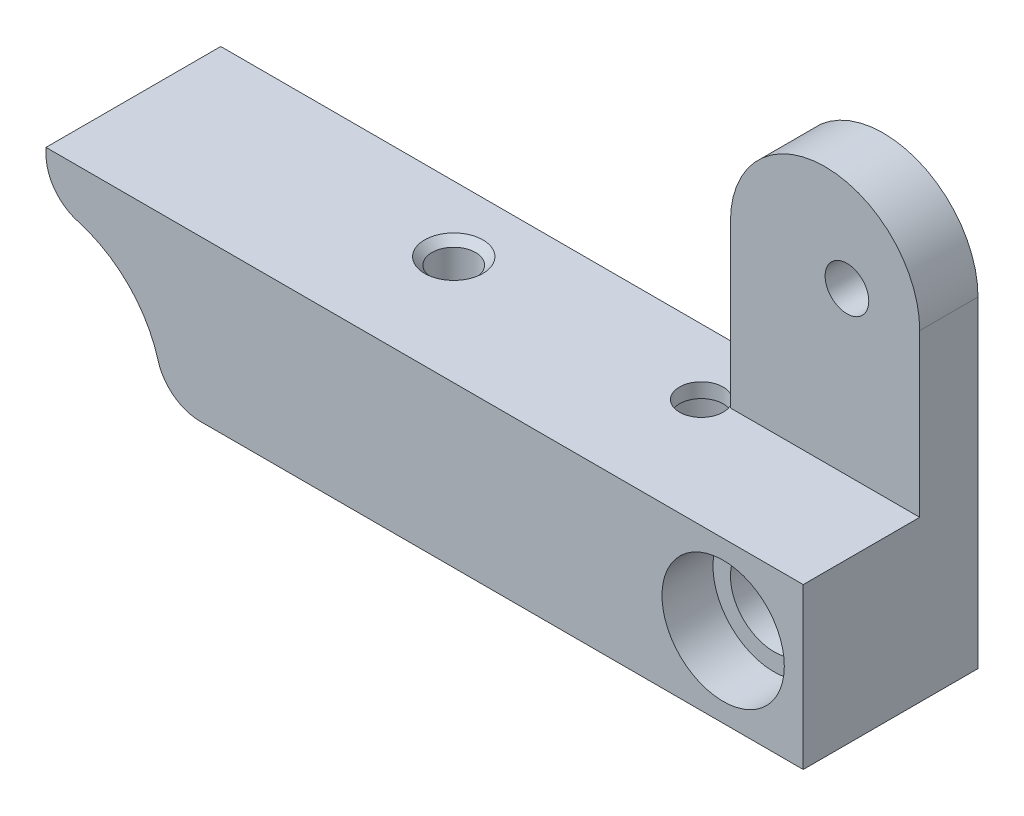
SolidWorks part; units mm, degrees
ref_plane "Front Plane" through (0, 0, 0) normal (0, 0, 1) x (1, 0, 0)
ref_plane "Top Plane" through (0, 0, 0) normal (0, 1, 0) x (1, 0, 0)
ref_plane "Right Plane" through (0, 0, 0) normal (1, 0, 0) x (0, 0, -1)
sketch "Sketch1" plane through (0, 0, 0) normal (0, 0, 1) x (1, 0, 0)
  line L0 (0, 0) -> (52, 0)
  line L3 (52, 0) -> (52, 11)
  line L4 (52, 11) -> (0, 11)
  line L7 (0, 11) -> (0, 0)
  point P2 (0.7988, 8.9006)
  point P3 (42, 0)
  point P7 (42, 8)
  point P8 (52, 0.379)
  dimension "D2" = 11
  dimension "D3" = 52
extrude "Boss-Extrude1" add sketch "Sketch1" along normal blind 12
sketch "Sketch3" plane through (0, 0, 0) normal (-1, 0, 0) x (0, 0, 1)
  line L0 (0, 0) -> (12, 0)
  line L1 (0, 11) -> (0, 0) construction
  line L2 (12, 11) -> (12, 0) construction
  line L3 (12, 0) -> (12, 8)
  line L4 (12, 8) -> (0, 8)
  line L5 (0, 8) -> (0, 0)
  line L6 (12, 11) -> (0, 11) construction
  dimension "D1" = 8
  dimension "D2" = 3
revolve "Cut-Revolve1" cut sketch "Sketch3" angle 90 about L0
sketch "Sketch4" plane through (0, 11, 0) normal (0, 1, 0) x (1, 0, 0)
  line L1 (52, 0) -> (39, 0)
  line L2 (52, 0) -> (52, -4)
  line L3 (52, -4) -> (39, -4)
  line L4 (39, 0) -> (39, -4)
  dimension "D1" = 4
  dimension "D2" = 13
extrude "Boss-Extrude2" add sketch "Sketch4" along normal blind 17.603
sketch "Sketch6" plane through (0, 0, 4) normal (0, 0, 1) x (1, 0, 0)
  line L0 (45.5, 28.603) -> (45.5, 11) construction
  line L1 (39, 28.603) -> (52, 28.603) construction
  line L2 (39, 11) -> (52, 11) construction
  line L3 (52, 22.103) -> (39, 22.103) construction
  line L4 (52, 28.603) -> (52, 11) construction
  line L5 (39, 28.603) -> (39, 11) construction
  line L6 (52, 22.103) -> (52, 28.603)
  line L7 (52, 28.603) -> (39, 28.603)
  line L8 (39, 28.603) -> (39, 22.103)
  circle A0 centre (45.5, 22.103) radius 6.5
  line M5 (52, 11) -> (52, 28.603)
  line M6 (52, 28.603) -> (39, 28.603)
  line M7 (39, 28.603) -> (39, 11)
  dimension "D1" = 13
  dimension "D2" = 6.5
extrude "Cut-Extrude1" cut sketch "Sketch6" against normal through all contours A0 M5 M6 | A0 L7 M7
sketch "Sketch7" plane through (0, 0, 4) normal (0, 0, 1) x (1, 0, 0)
  line L0 (52, 22.103) -> (47, 22.103) construction
  circle A0 centre (47, 22.103) radius 1.5
  dimension "D2" = 3
  dimension "D1" = 5
extrude "Cut-Extrude2" cut sketch "Sketch7" against normal through all
sketch "Sketch8" plane through (0, 0, 12) normal (0, 0, 1) x (1, 0, 0)
  line L0 (52, 0) -> (52, 11) construction
  line L1 (8, 0) -> (52, 0) construction
  circle A0 centre (46.5, 5.5) radius 4.2
  dimension "D1" = 8.4
  dimension "D2" = 5.5
  dimension "D3" = 5.5
extrude "Cut-Extrude3" cut sketch "Sketch8" against normal blind 3.5
sketch "Sketch9" plane through (0, 0, 8.5) normal (0, 0, 1) x (1, 0, 0)
  circle A0 centre (46.5, 5.5) radius 3
  dimension "D1" = 6
extrude "Cut-Extrude4" cut sketch "Sketch9" against normal blind 7.5
sketch "Sketch10" plane through (0, 0, 1) normal (0, 0, 1) x (1, 0, 0)
  circle A0 centre (46.5, 5.5) radius 1.6
  dimension "D1" = 3.2
extrude "Cut-Extrude5" cut sketch "Sketch10" against normal through all
sketch "Sketch11" plane through (0, 0, 0) normal (0, -1, 0) x (1, 0, 0)
  line L0 (52, 12) -> (52, 0) construction
  line L1 (8, 0) -> (52, 0) construction
  circle A0 centre (37.5, 4.5) radius 1.5
  circle A1 centre (20.5, 4.5) radius 1.5
  point P8 (0, 0)
  dimension "D3" = 3
  dimension "D5" = 3
  dimension "D1" = 14.5
  dimension "D2" = 4.5
  dimension "D4" = 31.5
extrude "Cut-Extrude6" cut sketch "Sketch11" against normal through all
sketch "Sketch13" plane through (0, 0, 0) normal (0, -1, 0) x (1, 0, 0)
  circle A0 centre (37.5, 4.5) radius 3
  dimension "D1" = 6
extrude "Cut-Extrude7" cut sketch "Sketch13" against normal blind 10
chamfer "Chamfer3" distance 0.5 angle 45 2 edges at (22, 11, 4.5) (20.5, 0, 3)
fillet "Fillet11" radius 3 1 edges at (0, 8, 6)
fillet "Fillet12" radius 3 1 edges at (8, 0, 6)
